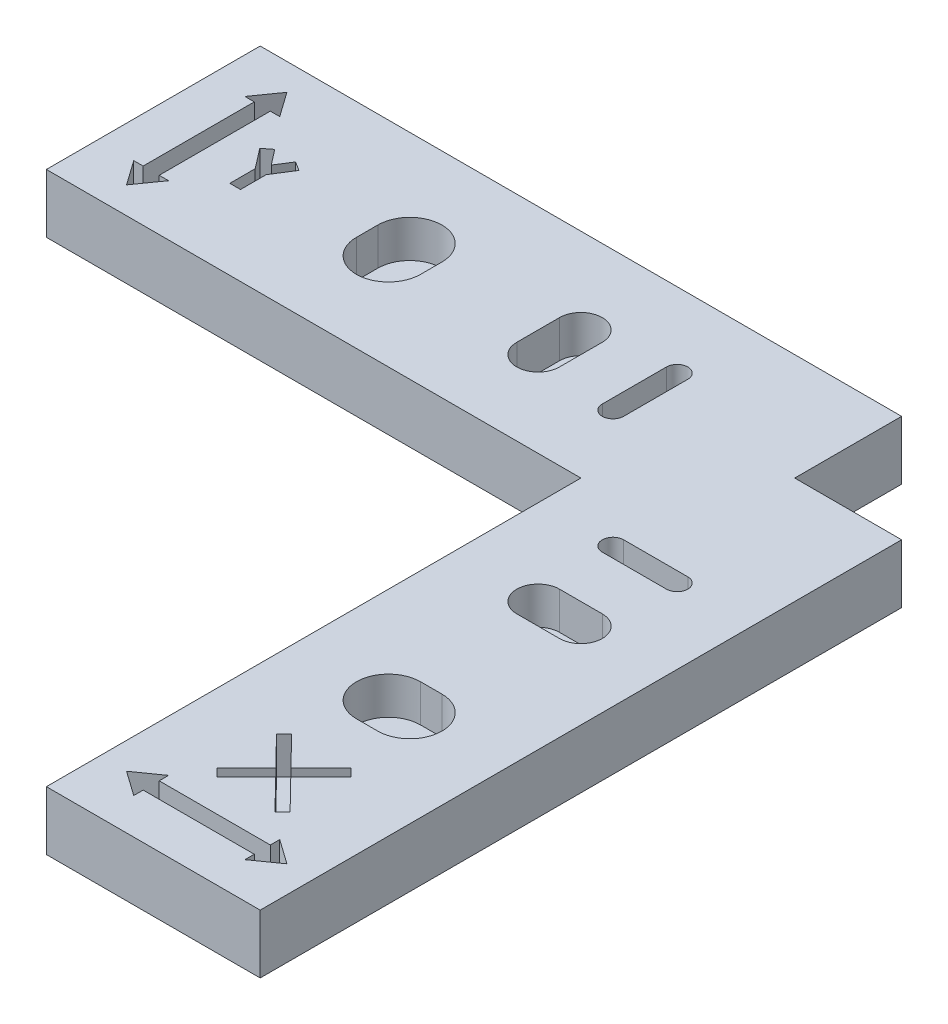
SolidWorks part; units mm, degrees
ref_plane "Front Plane" through (0, 0, 0) normal (0, 0, 1) x (1, 0, 0)
ref_plane "Top Plane" through (0, 0, 0) normal (0, 1, 0) x (1, 0, 0)
ref_plane "Right Plane" through (0, 0, 0) normal (1, 0, 0) x (0, 0, -1)
sketch "Sketch1" plane through (0, 0, 0) normal (0, 1, 0) x (1, 0, 0)
  line L0 (0, 0) -> (10, 10) construction
  line L1 (10, 10) -> (10, 20)
  line L2 (10, 20) -> (-50, 20)
  line L3 (-50, 20) -> (-50, 0)
  line L4 (-50, 0) -> (0, 0)
  line L5 (-50, 10) -> (-45, 10) construction
  line L6 (-45, 17.5) -> (-45, 2.5) construction
  line L7 (-45, 2.5) -> (-46.6308, 4.8028)
  line L8 (-46.6308, 4.8028) -> (-45.75, 4.8028)
  line L9 (-45.75, 4.8028) -> (-45.75, 15.1972)
  line L10 (-45, 2.5) -> (-43.3692, 4.8028)
  line L11 (-43.3692, 4.8028) -> (-44.25, 4.8028)
  line L12 (-44.25, 4.8028) -> (-44.25, 15.1972)
  line L13 (-46.6308, 15.1972) -> (-45.75, 15.1972)
  line L14 (-45, 17.5) -> (-46.6308, 15.1972)
  line L15 (-43.3692, 15.1972) -> (-44.25, 15.1972)
  line L16 (-45, 17.5) -> (-43.3692, 15.1972)
  line L17 (10, 10) -> (-45, 10) construction
  line L18 (-12, 12) -> (-12, 8) construction
  line L21 (-10, 12) -> (-10, 8)
  line L24 (-4, 13) -> (-4, 7) construction
  line L25 (-3, 13) -> (-3, 7)
  line L26 (-5, 13) -> (-5, 7)
  line L27 (-4, 14) -> (-12.8412, 14) construction
  line L28 (-4, 6) -> (-12.8412, 6) construction
  line L29 (-14, 12) -> (-14, 8)
  line L30 (-12, 14) -> (-17.5615, 14) construction
  line L31 (-12, 6) -> (-17.5615, 6) construction
  line L32 (-27, 11) -> (-27, 9) construction
  line L33 (-24, 11) -> (-24, 9)
  line L34 (-30, 11) -> (-30, 9)
  line L35 (-27, 14) -> (-24.7912, 14) construction
  line L36 (-27, 6) -> (-24.7912, 6) construction
  line L37 (6, -27) -> (6, -24.7912) construction
  line L38 (14, -27) -> (14, -24.7912) construction
  line L39 (6, -12) -> (6, -17.5615) construction
  line L40 (14, -12) -> (14, -17.5615) construction
  line L41 (6, -4) -> (6, -12.8412) construction
  line L42 (14, -4) -> (14, -12.8412) construction
  line L43 (10, 10) -> (10, -45) construction
  line L44 (17.5, -45) -> (2.5, -45) construction
  line L45 (10, -50) -> (10, -45) construction
  line L46 (17.5, -45) -> (15.1972, -43.3692)
  line L47 (15.1972, -43.3692) -> (15.1972, -44.25)
  line L48 (17.5, -45) -> (15.1972, -46.6308)
  line L49 (15.1972, -46.6308) -> (15.1972, -45.75)
  line L50 (4.8028, -44.25) -> (15.1972, -44.25)
  line L51 (4.8028, -43.3692) -> (4.8028, -44.25)
  line L52 (2.5, -45) -> (4.8028, -43.3692)
  line L53 (4.8028, -45.75) -> (15.1972, -45.75)
  line L54 (4.8028, -46.6308) -> (4.8028, -45.75)
  line L55 (2.5, -45) -> (4.8028, -46.6308)
  line L56 (0, -50) -> (0, 0)
  line L57 (20, -50) -> (0, -50)
  line L58 (20, 10) -> (20, -50)
  line L59 (10, 10) -> (20, 10)
  line L60 (13, -4) -> (7, -4) construction
  line L61 (13, -3) -> (7, -3)
  line L62 (13, -5) -> (7, -5)
  line L63 (11, -27) -> (9, -27) construction
  line L64 (11, -24) -> (9, -24)
  line L65 (11, -30) -> (9, -30)
  line L66 (12, -12) -> (8, -12) construction
  line L67 (12, -10) -> (8, -10)
  line L68 (12, -14) -> (8, -14)
  line L71 (-39.8363, 10.8716) -> (-40.9421, 12.3054)
  line L73 (-39.2955, 9.8553) -> (-38.1093, 11.7329)
  line L74 (-40.2955, 9.8296) -> (-40.2955, 7.4548)
  line L75 (-40.2955, 9.8296) -> (-41.7339, 11.6946)
  line L76 (-39.8363, 10.8716) -> (-38.9547, 12.2671)
  line L77 (-39.2955, 9.8553) -> (-39.2955, 7.4548)
  line L78 (-41.7339, 11.6946) -> (-40.9421, 12.3054)
  line L79 (-38.9547, 12.2671) -> (-38.1093, 11.7329)
  line L80 (-39.2955, 7.4548) -> (-40.2955, 7.4548)
  line L81 (6.8403, -40.8637) -> (13.0963, -34.6077)
  line L82 (6.8403, -34.6077) -> (13.0963, -41.0059)
  line L83 (6.4828, -34.9572) -> (12.7388, -41.3555)
  line L84 (7.1938, -41.2173) -> (13.4499, -34.9612)
  line L85 (7.1978, -34.2581) -> (13.4538, -40.6563)
  line L86 (6.4867, -40.5102) -> (12.7428, -34.2541)
  line L87 (12.7388, -41.3555) -> (13.4538, -40.6563)
  line L88 (13.4499, -34.9612) -> (12.7428, -34.2541)
  line L89 (7.1978, -34.2581) -> (6.4828, -34.9572)
  line L90 (6.4867, -40.5102) -> (7.1938, -41.2173)
  arc A4 (-3, 13) -> (-5, 13) centre (-4, 13) ccw
  arc A5 (-5, 7) -> (-3, 7) centre (-4, 7) ccw
  arc A6 (-10, 12) -> (-14, 12) centre (-12, 12) ccw
  arc A7 (-14, 8) -> (-10, 8) centre (-12, 8) ccw
  arc A8 (-24, 11) -> (-30, 11) centre (-27, 11) ccw
  arc A9 (-30, 9) -> (-24, 9) centre (-27, 9) ccw
  arc A10 (13, -3) -> (13, -5) centre (13, -4) cw
  arc A11 (7, -5) -> (7, -3) centre (7, -4) cw
  arc A12 (11, -24) -> (11, -30) centre (11, -27) cw
  arc A13 (9, -30) -> (9, -24) centre (9, -27) cw
  arc A14 (12, -10) -> (12, -14) centre (12, -12) cw
  arc A15 (8, -14) -> (8, -10) centre (8, -12) cw
  point P8 (-12, 10)
  point P11 (-46.1904, 4.8028)
  point P15 (-43.8096, 4.8028)
  point P17 (-45.75, 10)
  point P23 (-44.25, 10)
  point P33 (-27, 10)
  point P36 (-4, 10)
  point P92 (10, -4)
  point P99 (10, -27)
  point P104 (10, -44.25)
  point P105 (10, -45.75)
  point P106 (4.8028, -43.8096)
  point P109 (10, -12)
  dimension "D7" = 8
  dimension "D1" = 5
  dimension "D2" = 20
  dimension "D3" = 15
  dimension "D4" = 60
  dimension "D5" = 135
  dimension "D6" = 10
  dimension "D8" = 2
  dimension "D9" = 8
  dimension "D10" = 8
  dimension "D11" = 4
  dimension "D12" = 6
  dimension "D13" = 5
  dimension "D14" = 10
  dimension "D15" = 15
  dimension "D16" = 1.5
  dimension "D19" = 0.5
  dimension "D20" = 0.5
extrude "Boss-Extrude1" add sketch "Sketch1" along normal blind 3.5 contours L29 A7 L21 A6 | L34 A9 L33 A8 | L26 A5 L25 A4 | L80 L77 L73 L79 L76 L71 L78 L75 L74 | L16 L14 L13 L9 L8 L7 L10 L11 L12 L15 | A15 L68 A14 L67 | A11 L62 A10 L61 | A13 L65 A12 L64 | L86 L90 L81 L83 | L86 L83 L81 L82 | L86 L82 L81 L85 | L82 L89 L83 L86 | L85 L89 L82 L86 | L81 L88 L86 L85 | L84 L88 L81 L85 | L85 L81 L82 L84 | L83 L84 L82 L81 | L83 L87 L82 L84 | L82 L87 L85 L84 | L81 L90 L84 L83 | L52 L55 L54 L53 L49 L48 L46 L47 L50 L51 | L58 L57 L56 L4 L3 L2 L1 L59
sketch "Sketch2" plane through (0, 0, 0) normal (0, -1, 0) x (1, 0, 0)
  line L0 (20, 50) -> (0, 50) construction
  line L1 (0, 50) -> (0, 0) construction
  line L2 (20, -10) -> (20, 50) construction
  line L3 (10, -10) -> (20, -10) construction
  line L4 (10, -10) -> (10, -20) construction
  line L5 (10, -20) -> (-50, -20) construction
  line L6 (-50, -20) -> (-50, 0) construction
  line L7 (-50, 0) -> (0, 0) construction
  line L8 (20, 50) -> (0, 50)
  line L9 (0, 50) -> (0, 0)
  line L10 (20, -10) -> (20, 50)
  line L11 (10, -10) -> (20, -10)
  line L12 (10, -10) -> (10, -20)
  line L13 (10, -20) -> (-50, -20)
  line L14 (-50, -20) -> (-50, 0)
  line L15 (-50, 0) -> (0, 0)
extrude "Boss-Extrude3" add sketch "Sketch2" along normal blind 2
